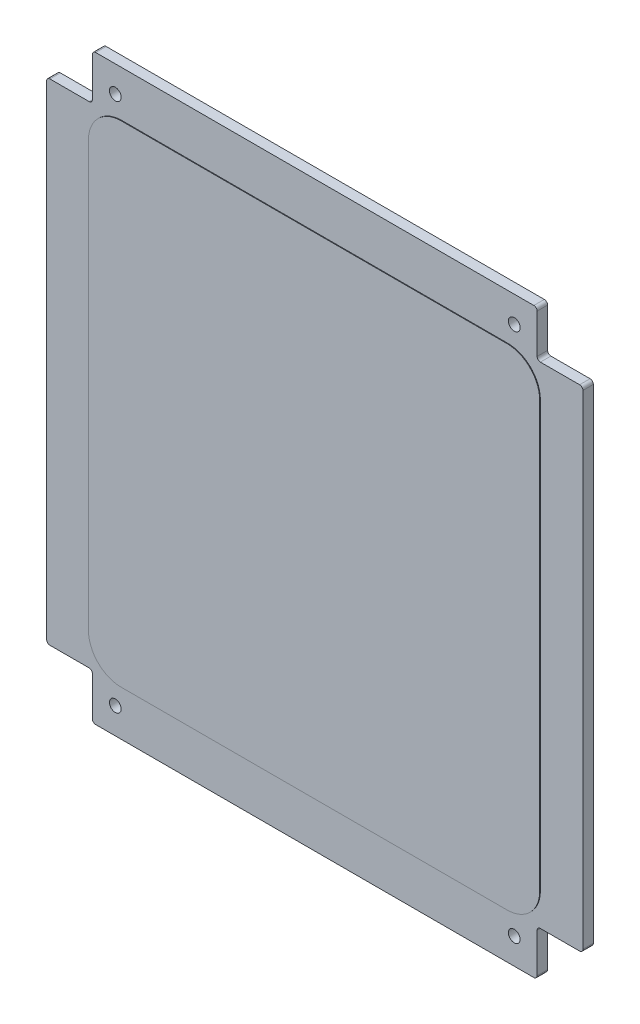
SolidWorks part; units mm, degrees
material "PET"
ref_plane "Front Plane" through (0, 0, 0) normal (0, 0, 1) x (1, 0, 0)
ref_plane "Top Plane" through (0, 0, 0) normal (0, 1, 0) x (1, 0, 0)
ref_plane "Right Plane" through (0, 0, 0) normal (1, 0, 0) x (0, 0, -1)
sketch "Sketch1" plane through (0, 0, 0) normal (0, 0, 1) x (1, 0, 0)
  line L0 (-34, 44) -> (-34, 38)
  line L1 (-33.5, -44.5) -> (33.5, -44.5)
  line L2 (-41, 37) -> (-41, -37)
  line L3 (-33.5, 44.5) -> (33.5, 44.5)
  line L4 (41, -37) -> (41, 37)
  line L5 (34, -44) -> (34, -38)
  line L6 (34.5, -37.5) -> (40.5, -37.5)
  line L7 (-34.5, 37.5) -> (-40.5, 37.5)
  line L8 (34, 44) -> (34, 38)
  line L9 (34.5, 37.5) -> (40.5, 37.5)
  line L10 (-40.5, -37.5) -> (-34.5, -37.5)
  line L11 (-34, -38) -> (-34, -44)
  line L12 (-34.5, -38) -> (34.5, 38) construction
  line L13 (34.5, -38) -> (-34.5, 38) construction
  arc A0 (-33.5, 44.5) -> (-34, 44) centre (-33.5, 44) ccw
  arc A1 (33.5, 44.5) -> (34, 44) centre (33.5, 44) cw
  arc A2 (34, 38) -> (34.5, 37.5) centre (34.5, 38) ccw
  arc A3 (40.5, 37.5) -> (41, 37) centre (40.5, 37) cw
  arc A4 (33.5, -44.5) -> (34, -44) centre (33.5, -44) ccw
  arc A5 (34.5, -37.5) -> (34, -38) centre (34.5, -38) ccw
  arc A6 (40.5, -37.5) -> (41, -37) centre (40.5, -37) ccw
  arc A7 (-34, -44) -> (-33.5, -44.5) centre (-33.5, -44) ccw
  arc A8 (-34, -38) -> (-34.5, -37.5) centre (-34.5, -38) ccw
  arc A9 (-41, -37) -> (-40.5, -37.5) centre (-40.5, -37) ccw
  arc A10 (-40.5, 37.5) -> (-41, 37) centre (-40.5, 37) ccw
  arc A11 (-34.5, 37.5) -> (-34, 38) centre (-34.5, 38) ccw
  point P0 (0, 0)
  dimension "D4" = 0.5
  dimension "D1" = 7
  dimension "D2" = 7
  dimension "D3" = 7
  dimension "D5" = 7
  dimension "D6" = 7
  dimension "D7" = 7
  dimension "D8" = 7
  dimension "D9" = 7
  dimension "D10" = 89
  dimension "D11" = 82
extrude "Boss-Extrude1" add sketch "Sketch1" along normal blind 1.6
sketch "Esboço1" plane through (0, 0, 1.6) normal (0, 0, 1) x (1, 0, 0)
  line L1 (-29.5, -37.5) -> (29.5, -37.5)
  line L2 (-34.5, -32.5) -> (-34.5, 32.5)
  line L3 (-29.5, 37.5) -> (29.5, 37.5)
  line L4 (34.5, -32.5) -> (34.5, 32.5)
  line L5 (-29.5, -32.5) -> (29.5, 32.5) construction
  line L6 (-29.5, 32.5) -> (29.5, -32.5) construction
  arc A0 (-34.5, 32.5) -> (-29.5, 37.5) centre (-29.5, 32.5) cw
  arc A1 (29.5, 37.5) -> (34.5, 32.5) centre (29.5, 32.5) cw
  arc A2 (34.5, -32.5) -> (29.5, -37.5) centre (29.5, -32.5) cw
  arc A3 (-29.5, -37.5) -> (-34.5, -32.5) centre (-29.5, -32.5) cw
  point P0 (0, 0)
  dimension "D1" = 5
  dimension "D2" = 69
  dimension "D3" = 75
extrude "Boss-Extrude2" add sketch "Esboço1" along normal blind 0.1
hole_wizard "M1.6 Hole1-FixingStructure" positions "Sketch3" profile "Sketch2" hole size "M1.6" standard "DIN"
sketch "Sketch3" plane through (0, 0, 0) normal (0, 0, -1) x (-1, 0, 0)
  line L0 (-33.5, 44.5) -> (33.5, 44.5) construction
  line L1 (33.5, -44.5) -> (-33.5, -44.5) construction
  line L2 (-41, -37) -> (-41, 37) construction
  line L3 (41, 37) -> (41, -37) construction
  point P0 (-30.5, 40.5)
  point P2 (30.5, 40.5)
  point P4 (-30.5, -40.5)
  point P6 (30.5, -40.5)
  dimension "D1" = 4
  dimension "D2" = 4
  dimension "D3" = 10.5
  dimension "D4" = 10.5
sketch "Sketch2" plane through (30.5, 40.5, 0) normal (1, 0, 0) x (0, 1, 0)
  line L0 (0, 0) -> (0, 200.5408)
  line L1 (0, 200.5408) -> (0.9, 200)
  line L2 (0.9, 200) -> (0.9, 0)
  line L5 (0.9, 0) -> (0, 0)
  line L10 (0, 200.5408) -> (-0.9, 200) construction
  line L11 (0, -6.35) -> (0, 107.95) construction
  dimension "Hole Dia." = 1.8
  dimension "Hole Depth" = 200
  dimension "Drill Angle" = 118
